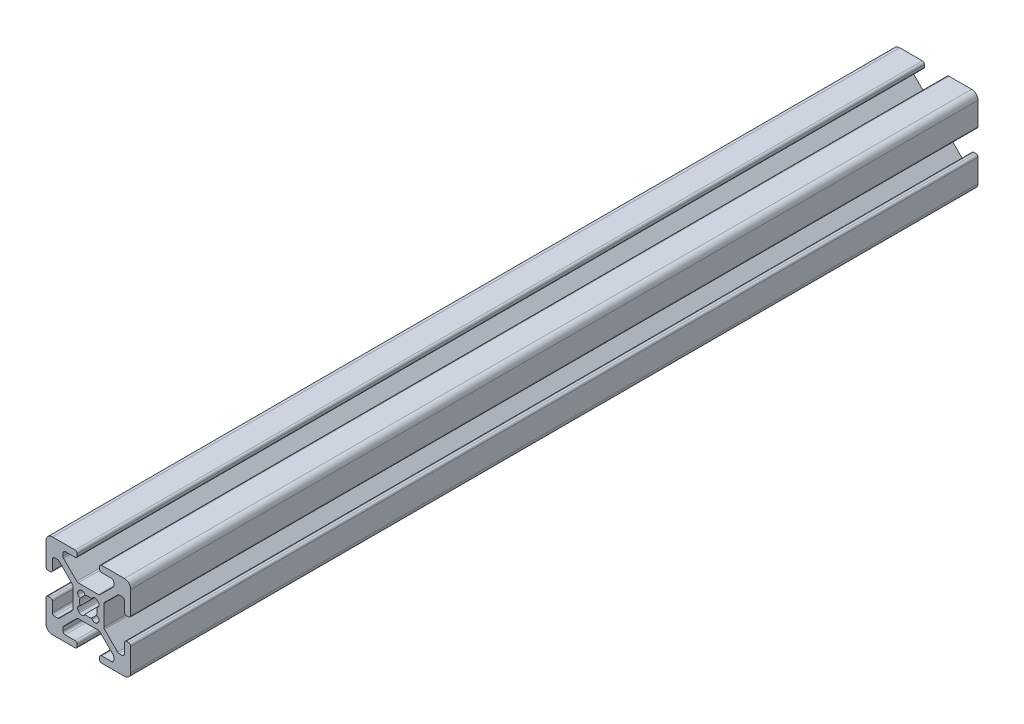
SolidWorks part; units mm, degrees
material "Alumina"
ref_plane "Front Plane" through (0, 0, 0) normal (0, 0, 1) x (1, 0, 0)
ref_plane "Top Plane" through (0, 0, 0) normal (0, 1, 0) x (1, 0, 0)
ref_plane "Right Plane" through (0, 0, 0) normal (1, 0, 0) x (0, 0, -1)
ref_plane "Plane1" through (0, 0, 4000) normal (0, 0, 1) x (1, 0, 0)
sketch "Sketch1" plane through (0, 0, 4000) normal (0, 0, 1) x (1, 0, 0)
  line B0 (10, 3.138) -> (10, 8.5)
  line B1 (8.5, 10) -> (3.138, 10)
  line B2 (2.63, 9.492) -> (2.63, 9.008)
  line B3 (3.138, 8.5) -> (5.487, 8.5)
  line B4 (5.995, 7.992) -> (5.995, 7.2661)
  line B5 (5.8462, 6.9069) -> (2.7431, 3.8038)
  line B6 (2.3839, 3.655) -> (-2.3839, 3.655)
  line B7 (-2.7431, 3.8038) -> (-5.8462, 6.9069)
  line B8 (-5.995, 7.2661) -> (-5.995, 7.992)
  line B9 (-5.487, 8.5) -> (-3.138, 8.5)
  line B10 (-2.63, 9.008) -> (-2.63, 9.492)
  line B11 (-3.138, 10) -> (-8.5, 10)
  line B12 (-10, 8.5) -> (-10, 3.138)
  line B13 (-9.492, 2.63) -> (-9.008, 2.63)
  line B14 (-8.5, 3.138) -> (-8.5, 5.487)
  line B15 (-7.992, 5.995) -> (-7.2661, 5.995)
  line B16 (-6.9069, 5.8462) -> (-3.8038, 2.7431)
  line B17 (-3.655, 2.3839) -> (-3.655, -2.3839)
  line B18 (-3.8038, -2.7431) -> (-6.9069, -5.8462)
  line B19 (-7.2661, -5.995) -> (-7.992, -5.995)
  line B20 (-8.5, -5.487) -> (-8.5, -3.138)
  line B21 (-9.008, -2.63) -> (-9.492, -2.63)
  line B22 (-10, -3.138) -> (-10, -8.5)
  line B23 (-8.5, -10) -> (-3.138, -10)
  line B24 (-2.63, -9.492) -> (-2.63, -9.008)
  line B25 (-3.138, -8.5) -> (-5.487, -8.5)
  line B26 (-5.995, -7.992) -> (-5.995, -7.2661)
  line B27 (-5.8462, -6.9069) -> (-2.7431, -3.8038)
  line B28 (-2.3839, -3.655) -> (2.3839, -3.655)
  line B29 (2.7431, -3.8038) -> (5.8462, -6.9069)
  line B30 (5.995, -7.2661) -> (5.995, -7.992)
  line B31 (5.487, -8.5) -> (3.138, -8.5)
  line B32 (2.63, -9.008) -> (2.63, -9.492)
  line B33 (3.138, -10) -> (8.5, -10)
  line B34 (10, -8.5) -> (10, -3.138)
  line B35 (9.492, -2.63) -> (9.008, -2.63)
  line B36 (8.5, -3.138) -> (8.5, -5.487)
  line B37 (7.992, -5.995) -> (7.2661, -5.995)
  line B38 (6.9069, -5.8462) -> (3.8038, -2.7431)
  line B39 (3.655, -2.3839) -> (3.655, 2.3839)
  line B40 (3.8038, 2.7431) -> (6.9069, 5.8462)
  line B41 (7.2661, 5.995) -> (7.992, 5.995)
  line B42 (8.5, 5.487) -> (8.5, 3.138)
  line B43 (9.008, 2.63) -> (9.492, 2.63)
  line B44 (-2.1249, -2.3045) -> (-2.3045, -2.1249)
  line B45 (-2.3045, 2.1249) -> (-2.1249, 2.3045)
  line B46 (2.1249, 2.3045) -> (2.3045, 2.1249)
  line B47 (2.3045, -2.1249) -> (2.1249, -2.3045)
  arc B48 (9.492, 2.63) -> (10, 3.138) centre (9.492, 3.138) ccw
  arc B49 (10, 8.5) -> (8.5, 10) centre (8.5, 8.5) ccw
  arc B50 (3.138, 10) -> (2.63, 9.492) centre (3.138, 9.492) ccw
  arc B51 (2.63, 9.008) -> (3.138, 8.5) centre (3.138, 9.008) ccw
  arc B52 (5.487, 8.5) -> (5.995, 7.992) centre (5.487, 7.992) cw
  arc B53 (5.995, 7.2661) -> (5.8462, 6.9069) centre (5.487, 7.2661) cw
  arc B54 (2.7431, 3.8038) -> (2.3839, 3.655) centre (2.3839, 4.163) cw
  arc B55 (-2.3839, 3.655) -> (-2.7431, 3.8038) centre (-2.3839, 4.163) cw
  arc B56 (-5.8462, 6.9069) -> (-5.995, 7.2661) centre (-5.487, 7.2661) cw
  arc B57 (-5.995, 7.992) -> (-5.487, 8.5) centre (-5.487, 7.992) cw
  arc B58 (-3.138, 8.5) -> (-2.63, 9.008) centre (-3.138, 9.008) ccw
  arc B59 (-2.63, 9.492) -> (-3.138, 10) centre (-3.138, 9.492) ccw
  arc B60 (-8.5, 10) -> (-10, 8.5) centre (-8.5, 8.5) ccw
  arc B61 (-10, 3.138) -> (-9.492, 2.63) centre (-9.492, 3.138) ccw
  arc B62 (-9.008, 2.63) -> (-8.5, 3.138) centre (-9.008, 3.138) ccw
  arc B63 (-8.5, 5.487) -> (-7.992, 5.995) centre (-7.992, 5.487) cw
  arc B64 (-7.2661, 5.995) -> (-6.9069, 5.8462) centre (-7.2661, 5.487) cw
  arc B65 (-3.8038, 2.7431) -> (-3.655, 2.3839) centre (-4.163, 2.3839) cw
  arc B66 (-3.655, -2.3839) -> (-3.8038, -2.7431) centre (-4.163, -2.3839) cw
  arc B67 (-6.9069, -5.8462) -> (-7.2661, -5.995) centre (-7.2661, -5.487) cw
  arc B68 (-7.992, -5.995) -> (-8.5, -5.487) centre (-7.992, -5.487) cw
  arc B69 (-8.5, -3.138) -> (-9.008, -2.63) centre (-9.008, -3.138) ccw
  arc B70 (-9.492, -2.63) -> (-10, -3.138) centre (-9.492, -3.138) ccw
  arc B71 (-10, -8.5) -> (-8.5, -10) centre (-8.5, -8.5) ccw
  arc B72 (-3.138, -10) -> (-2.63, -9.492) centre (-3.138, -9.492) ccw
  arc B73 (-2.63, -9.008) -> (-3.138, -8.5) centre (-3.138, -9.008) ccw
  arc B74 (-5.487, -8.5) -> (-5.995, -7.992) centre (-5.487, -7.992) cw
  arc B75 (-5.995, -7.2661) -> (-5.8462, -6.9069) centre (-5.487, -7.2661) cw
  arc B76 (-2.7431, -3.8038) -> (-2.3839, -3.655) centre (-2.3839, -4.163) cw
  arc B77 (2.3839, -3.655) -> (2.7431, -3.8038) centre (2.3839, -4.163) cw
  arc B78 (5.8462, -6.9069) -> (5.995, -7.2661) centre (5.487, -7.2661) cw
  arc B79 (5.995, -7.992) -> (5.487, -8.5) centre (5.487, -7.992) cw
  arc B80 (3.138, -8.5) -> (2.63, -9.008) centre (3.138, -9.008) ccw
  arc B81 (2.63, -9.492) -> (3.138, -10) centre (3.138, -9.492) ccw
  arc B82 (8.5, -10) -> (10, -8.5) centre (8.5, -8.5) ccw
  arc B83 (10, -3.138) -> (9.492, -2.63) centre (9.492, -3.138) ccw
  arc B84 (9.008, -2.63) -> (8.5, -3.138) centre (9.008, -3.138) ccw
  arc B85 (8.5, -5.487) -> (7.992, -5.995) centre (7.992, -5.487) cw
  arc B86 (7.2661, -5.995) -> (6.9069, -5.8462) centre (7.2661, -5.487) cw
  arc B87 (3.8038, -2.7431) -> (3.655, -2.3839) centre (4.163, -2.3839) cw
  arc B88 (3.655, 2.3839) -> (3.8038, 2.7431) centre (4.163, 2.3839) cw
  arc B89 (6.9069, 5.8462) -> (7.2661, 5.995) centre (7.2661, 5.487) cw
  arc B90 (7.992, 5.995) -> (8.5, 5.487) centre (7.992, 5.487) cw
  arc B91 (8.5, 3.138) -> (9.008, 2.63) centre (9.008, 3.138) ccw
  arc B92 (0.804, -1.9351) -> (-0.804, -1.9351) centre (0, 0) cw
  arc B93 (-0.804, -1.9351) -> (-2.1249, -2.3045) centre (-1.5684, -1.748) cw
  arc B94 (-2.3045, -2.1249) -> (-1.9351, -0.804) centre (-1.748, -1.5684) cw
  arc B95 (-1.9351, -0.804) -> (-1.9351, 0.804) centre (0, 0) cw
  arc B96 (-1.9351, 0.804) -> (-2.3045, 2.1249) centre (-1.748, 1.5684) cw
  arc B97 (-2.1249, 2.3045) -> (-0.804, 1.9351) centre (-1.5684, 1.748) cw
  arc B98 (-0.804, 1.9351) -> (0.804, 1.9351) centre (0, 0) cw
  arc B99 (0.804, 1.9351) -> (2.1249, 2.3045) centre (1.5684, 1.748) cw
  arc B100 (2.3045, 2.1249) -> (1.9351, 0.804) centre (1.748, 1.5684) cw
  arc B101 (1.9351, 0.804) -> (1.9351, -0.804) centre (0, 0) cw
  arc B102 (1.9351, -0.804) -> (2.3045, -2.1249) centre (1.748, -1.5684) cw
  arc B103 (2.1249, -2.3045) -> (0.804, -1.9351) centre (1.5684, -1.748) cw
sketch_block_instance "Block1-1"
sketch_block "Block1"
extrude "Boss-Extrude1" add sketch "Sketch1" against normal blind 200
